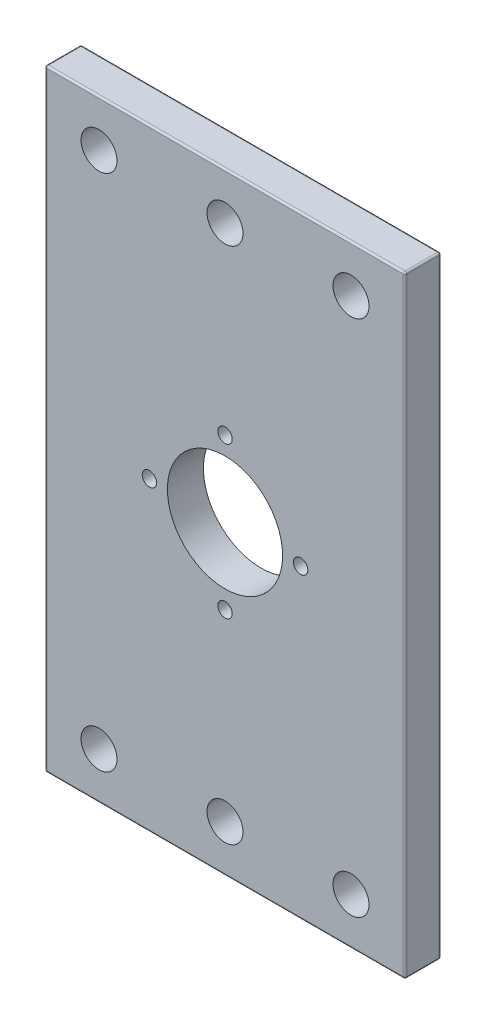
SolidWorks part; units mm, degrees
material "1060 合金"
ref_plane "前视基准面" through (0, 0, 0) normal (0, 0, 1) x (1, 0, 0)
ref_plane "上视基准面" through (0, 0, 0) normal (0, 1, 0) x (1, 0, 0)
ref_plane "右视基准面" through (0, 0, 0) normal (1, 0, 0) x (0, 0, -1)
sketch "草图1" plane through (0, 0, 0) normal (0, 0, 1) x (1, 0, 0)
  line L5 (50, -85) -> (-50, -85)
  line L9 (50, 85) -> (-50, 85)
  line L14 (50, 0) -> (50, -85)
  line L15 (-50, -85) -> (-50, -20)
  line L18 (50, 0) -> (50, 85)
  line L19 (-50, -20) -> (-50, 85)
  dimension "D1" = 100
  dimension "D2" = 85
  dimension "D3" = 85
  dimension "D4" = 0
  dimension "D5" = 50
extrude "凸台-拉伸1" add sketch "草图1" along normal blind 10 contours L9 L19 L15 L5 L14 L18
sketch "草图2" plane through (0, 0, 10) normal (0, 0, 1) x (1, 0, 0)
  circle A0 centre (0, 0) radius 16
extrude "切除-拉伸1" cut sketch "草图2" against normal blind 10
sketch "草图3" plane through (0, 0, 10) normal (0, 0, 1) x (1, 0, 0)
  circle A0 centre (0, -72) radius 5
  circle A1 centre (35, -72) radius 5
  circle A2 centre (-35, -72) radius 5
  point P6 (0, 0)
  point P7 (0, 0)
  dimension "D1" = 72
  dimension "D2" = 72
  dimension "D3" = 72
  dimension "D4" = 35
  dimension "D5" = 35
  dimension "D6" = 0
extrude "切除-拉伸2" cut sketch "草图3" against normal blind 10
sketch "草图6" plane through (0, 0, 10) normal (0, 0, 1) x (1, 0, 0)
  circle A0 centre (0, 21) radius 2
extrude "切除-拉伸4" cut sketch "草图6" against normal blind 10
pattern_circular "阵列(圆周)1" count 4 over 360 about axis through (0, 0, 0) along (0, 0, 1) of "切除-拉伸4"
mirror "镜向1" about plane through (0, 0, 0) normal (0, 1, 0) of "切除-拉伸2"
fillet "圆角1" radius 0.5 12 edges at (50, -85, 5) (-50, -85, 5) (-50, 85, 5) (50, 85, 5) (0, 85, 0) (0, 85, 10) (50, 0, 0) (50, 0, 10) (-50, 0, 0) (-50, 0, 10) (0, -85, 0) (0, -85, 10)
